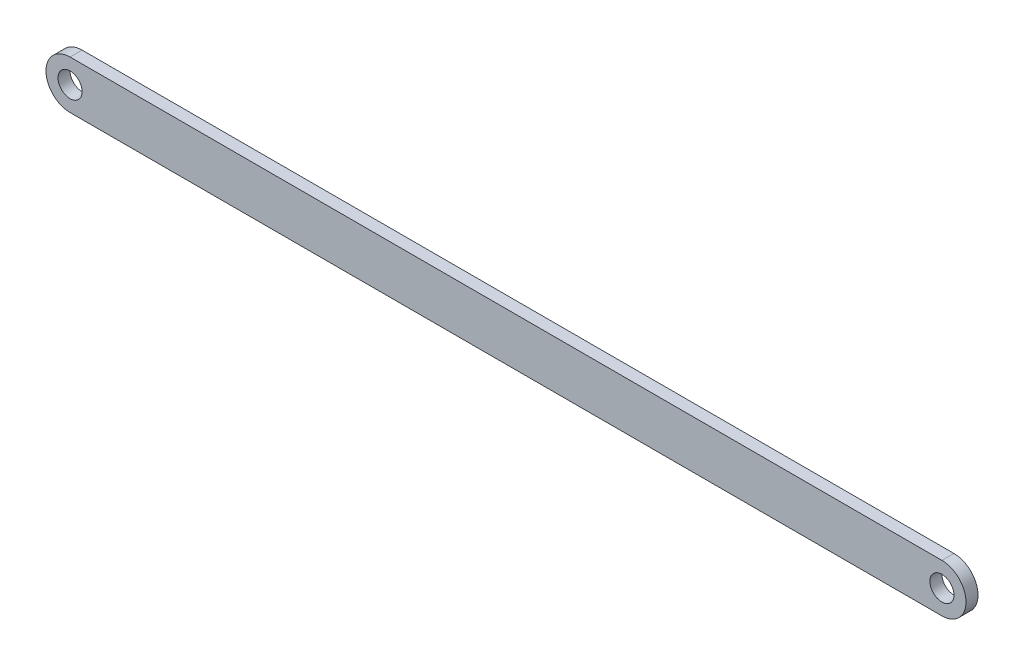
SolidWorks part; units mm, degrees
ref_plane "前视基准面" through (0, 0, 0) normal (0, 0, 1) x (1, 0, 0)
ref_plane "上视基准面" through (0, 0, 0) normal (0, 1, 0) x (1, 0, 0)
ref_plane "右视基准面" through (0, 0, 0) normal (1, 0, 0) x (0, 0, -1)
sketch "草图1" plane through (0, 0, 0) normal (0, 0, 1) x (1, 0, 0)
  line L0 (-21.6561, -0.3822) -> (268.3439, -0.3822) construction
  line L1 (-21.6561, 7.6178) -> (268.3439, 7.6178)
  line L2 (-21.6561, -8.3822) -> (268.3439, -8.3822)
  arc A0 (-21.6561, 7.6178) -> (-21.6561, -8.3822) centre (-21.6561, -0.3822) ccw
  arc A1 (268.3439, -8.3822) -> (268.3439, 7.6178) centre (268.3439, -0.3822) ccw
  circle A2 centre (-21.6561, -0.3822) radius 4
  circle A3 centre (268.3439, -0.3822) radius 4
  point P2 (123.3439, -0.3822)
  dimension "D1" = 8
  dimension "D3" = 8
  dimension "D4" = 8
  dimension "D2" = 290
extrude "凸台-拉伸1" add sketch "草图1" along normal blind 4
